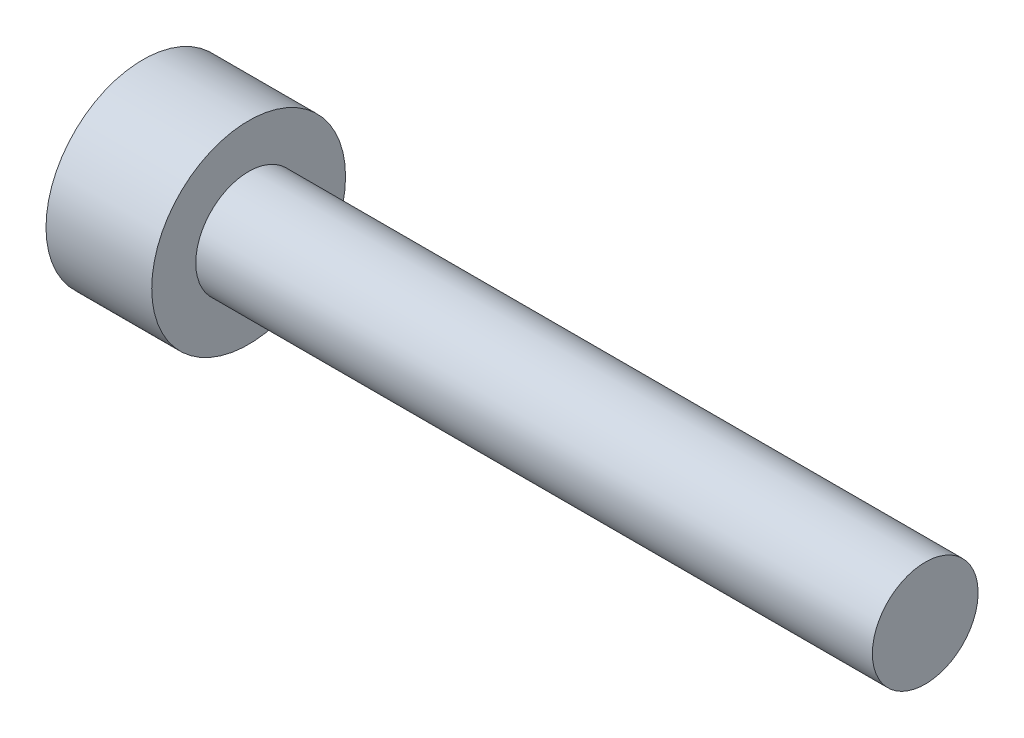
SolidWorks part; units mm, degrees
material "AISI Type 316L stainless steel"
ref_plane "Front Plane" through (0, 0, 0) normal (0, 0, 1) x (1, 0, 0)
ref_plane "Top Plane" through (0, 0, 0) normal (0, 1, 0) x (1, 0, 0)
ref_plane "Right Plane" through (0, 0, 0) normal (1, 0, 0) x (0, 0, -1)
sketch "Axial profile (mm)" plane through (0, 0, 0) normal (0, 0, 1) x (1, 0, 0)
  line L0 (-110, 0) -> (75, 0) construction
  line L1 (131.5, 0) -> (153.7, 0)
  line L2 (153.7, 0) -> (153.7, 1.5)
  line L3 (153.7, 1.5) -> (134.5, 1.5)
  line L4 (134.5, 1.5) -> (134.5, 2.75)
  line L5 (134.5, 2.75) -> (131.5, 2.75)
  line L6 (131.5, 2.75) -> (131.5, 0)
revolve "Full revolution" add sketch "Axial profile (mm)" angle 360 about L0
